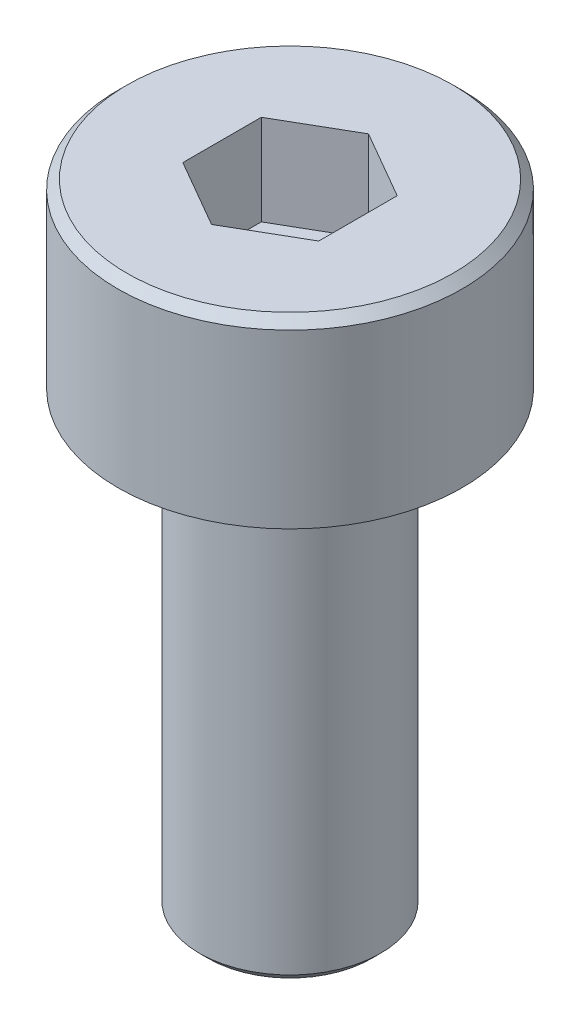
SolidWorks part; units mm, degrees
material "AISI 316, barra ricotta (SS)"
ref_plane "Piano frontale" through (0, 0, 0) normal (0, 0, 1) x (1, 0, 0)
ref_plane "Piano superiore" through (0, 0, 0) normal (0, 1, 0) x (1, 0, 0)
ref_plane "Piano destro" through (0, 0, 0) normal (1, 0, 0) x (0, 0, -1)
sketch "Schizzo1" plane through (0, 0, 0) normal (0, 0, 1) x (1, 0, 0)
  line L0 (0, 0) -> (0, 2)
  line L1 (0, 2) -> (1.9, 2)
  line L2 (1.9, 2) -> (1.9, 0)
  line L3 (1.9, 0) -> (1, 0)
  line L4 (1, 0) -> (1, -5)
  line L5 (1, -5) -> (0, -5)
  line L6 (0, -5) -> (0, 0)
  line L7 (0, 28.3885) -> (0, -27.6749) construction
  dimension "D1" = 2
  dimension "D2" = 2
  dimension "D3" = 3.8
  dimension "D4" = 5
revolve "Rivoluzione1" add sketch "Schizzo1" angle 360 about L7
chamfer "Smusso1" distance 0.1 angle 45 2 edges at (0, 2, 1.9) (0, -5, 1)
sketch "Schizzo2" plane through (0, 2, 0) normal (0, 1, 0) x (1, 0, 0)
  line L1 (0, 0.866) -> (-0.75, 0.433)
  line L2 (-0.75, 0.433) -> (-0.75, -0.433)
  line L3 (-0.75, -0.433) -> (0, -0.866)
  line L4 (0, -0.866) -> (0.75, -0.433)
  line L5 (0.75, -0.433) -> (0.75, 0.433)
  line L6 (0.75, 0.433) -> (0, 0.866)
  circle A0 centre (0, 0) radius 0.75 construction
  dimension "D1" = 1.5
extrude "Taglio-Estrusione1" cut sketch "Schizzo2" against normal blind 1
